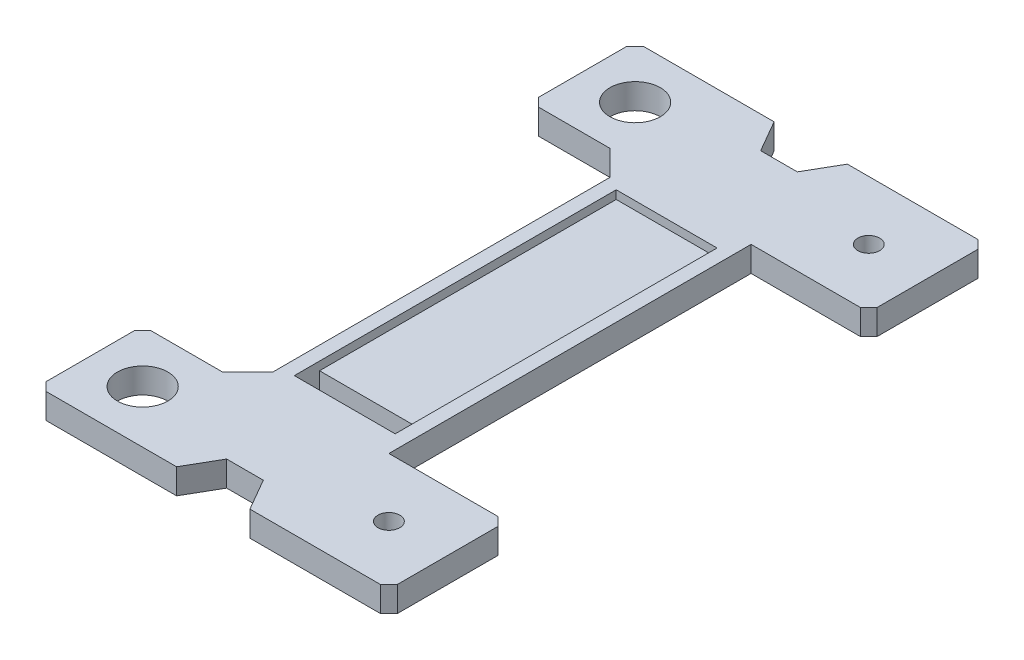
SolidWorks part; units mm, degrees
ref_plane "Front Plane" through (0, 0, 0) normal (0, 0, 1) x (1, 0, 0)
ref_plane "Top Plane" through (0, 0, 0) normal (0, 1, 0) x (1, 0, 0)
ref_plane "Right Plane" through (0, 0, 0) normal (1, 0, 0) x (0, 0, -1)
sketch "Sketch1" plane through (0, 0, 0) normal (0, 1, 0) x (1, 0, 0)
  line L0 (0, 23.05) -> (0, -23.05)
  line L1 (0, -23.05) -> (-12.5, -23.05)
  line L2 (-12.5, -23.05) -> (-12.5, -35.55)
  line L3 (-12.5, -35.55) -> (29.3, -35.55)
  line L4 (29.3, -35.55) -> (29.3, -21.55)
  line L5 (29.3, -21.55) -> (15.3, -21.55)
  line L6 (15.3, -21.55) -> (15.3, 21.55)
  line L7 (15.3, 21.55) -> (29.3, 21.55)
  line L8 (29.3, 21.55) -> (29.3, 35.55)
  line L10 (29.3, 35.55) -> (-12.5, 35.55)
  line L11 (-12.5, 35.55) -> (-12.5, 23.05)
  line L12 (-12.5, 23.05) -> (0, 23.05)
  point P10 (0, 0)
  point P14 (18.9408, 41.2392)
  dimension "D1" = 43.1
  dimension "D2" = 14
  dimension "D3" = 14
  dimension "D4" = 14
  dimension "D5" = 14
  dimension "D6" = 15.3
  dimension "D7" = 12.5
  dimension "D8" = 12.5
  dimension "D9" = 12.5
  dimension "D10" = 12.5
extrude "Boss-Extrude1" add sketch "Sketch1" along normal blind 3
sketch "Sketch2" plane through (0, 3, 0) normal (0, 1, 0) x (1, 0, 0)
  line L0 (-6.25, 23.05) -> (-6.25, -37.5297) construction
  line L4 (-12.5, 23.05) -> (0, 23.05) construction
  line L5 (-6.25, 23.05) -> (-6.25, 36.5382) construction
  line L6 (-12.5, 29.3) -> (2.6606, 29.3) construction
  line L7 (-12.5, 35.55) -> (-12.5, 23.05) construction
  line L8 (-12.5, -29.3) -> (1.2542, -29.3) construction
  line L9 (-12.5, -23.05) -> (-12.5, -35.55) construction
  line L10 (22.3, 21.55) -> (22.3, -37.5297) construction
  line L11 (15.3, 21.55) -> (29.3, 21.55) construction
  line L12 (22.3, 21.55) -> (22.3, 38.8755) construction
  line L13 (29.3, 28.55) -> (15.3774, 28.55) construction
  line L14 (29.3, 21.55) -> (29.3, 35.55) construction
  line L15 (29.3, -28.55) -> (12.5465, -28.55) construction
  line L16 (29.3, -35.55) -> (29.3, -21.55) construction
  circle A0 centre (-6.25, 29.3) radius 3
  circle A1 centre (-6.25, -29.3) radius 3
  circle A2 centre (22.3, -28.55) radius 1.3
  circle A3 centre (22.3, 28.55) radius 1.3
  dimension "D1" = 6
  dimension "D2" = 6
  dimension "D3" = 2.6
  dimension "D4" = 2.6
extrude "Cut-Extrude1" cut sketch "Sketch2" against normal through all
sketch "Sketch3" plane through (0, 3, 0) normal (0, 1, 0) x (1, 0, 0)
  line L0 (7.65, 0) -> (7.65, 35.55) construction
  line L1 (0, 0) -> (15.3, 0) construction
  line L3 (1.65, 19.15) -> (13.65, 19.15)
  line L4 (1.65, 19.15) -> (1.65, -19.15)
  line L5 (1.65, -19.15) -> (13.65, -19.15)
  line L6 (13.65, 19.15) -> (13.65, -19.15)
  line L9 (15.3, -21.55) -> (15.3, 21.55) construction
  line L10 (29.3, 35.55) -> (-12.5, 35.55) construction
  point P10 (7.65, 19.15)
  dimension "D1" = 12
  dimension "D2" = 38.3
extrude "Cut-Extrude2" cut sketch "Sketch3" against normal blind 1
sketch "Sketch4" plane through (0, 2, 0) normal (0, 1, 0) x (1, 0, 0)
  line L0 (13.65, -19.15) -> (13.65, 19.15) construction
  line L1 (1.65, -19.15) -> (13.65, -19.15)
  line L2 (1.65, -19.15) -> (1.65, -16.15)
  line L3 (1.65, -16.15) -> (13.65, -16.15)
  line L4 (13.65, -19.15) -> (13.65, -16.15)
  dimension "D1" = 3
extrude "Cut-Extrude3" cut sketch "Sketch4" against normal through all
chamfer "Chamfer1" distance 3 angle 45 2 edges at (0, 1.5, 23.05) (0, 1.5, -23.05)
sketch "Sketch5" plane through (0, 3, 0) normal (0, 1, 0) x (1, 0, 0)
  line L0 (-12.5, -35.55) -> (29.3, -35.55) construction
  line L1 (4.0372, -35.55) -> (6.2186, -39.3283)
  line L2 (6.2186, -39.3283) -> (10.5814, -39.3283)
  line L3 (10.5814, -39.3283) -> (12.7628, -35.55)
  line L4 (12.7628, -35.55) -> (10.5814, -31.7717)
  line L5 (10.5814, -31.7717) -> (6.2186, -31.7717)
  line L6 (6.2186, -31.7717) -> (4.0372, -35.55)
  line L7 (29.3, 35.55) -> (-12.5, 35.55) construction
  line L8 (4.0372, 35.55) -> (6.2186, 31.7717)
  line L9 (6.2186, 31.7717) -> (10.5814, 31.7717)
  line L10 (10.5814, 31.7717) -> (12.7628, 35.55)
  line L11 (12.7628, 35.55) -> (10.5814, 39.3283)
  line L12 (10.5814, 39.3283) -> (6.2186, 39.3283)
  line L13 (6.2186, 39.3283) -> (4.0372, 35.55)
  circle A0 centre (8.4, -35.55) radius 3.7783 construction
  circle A1 centre (8.4, 35.55) radius 3.7783 construction
extrude "Cut-Extrude4" cut sketch "Sketch5" against normal through all
chamfer "Chamfer2" distance 1 angle 45 8 edges at (-12.5, 1.5, 35.55) (-12.5, 1.5, 23.05) (-12.5, 1.5, -23.05) (-12.5, 1.5, -35.55) (29.3, 1.5, 35.55) (29.3, 1.5, 21.55) (29.3, 1.5, -35.55) (29.3, 1.5, -21.55)
